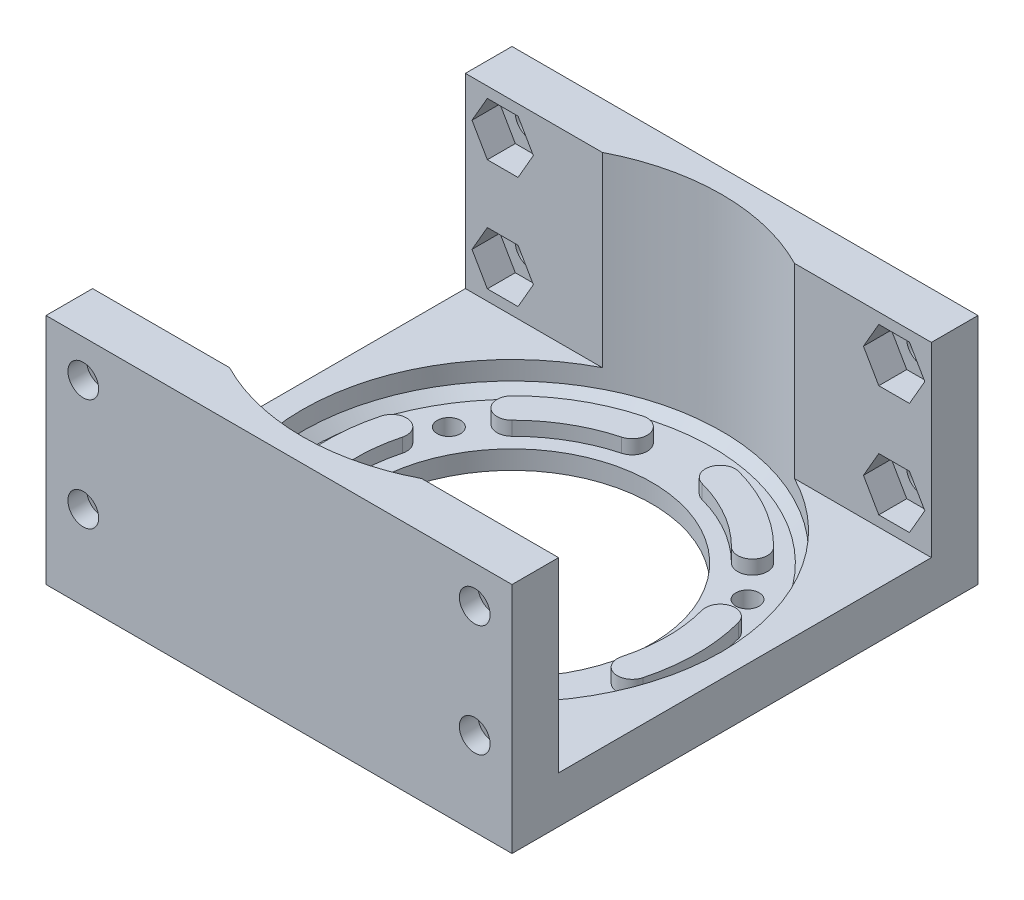
SolidWorks part; units mm, degrees
ref_plane "前视基准面" through (0, 0, 0) normal (0, 0, 1) x (1, 0, 0)
ref_plane "上视基准面" through (0, 0, 0) normal (0, 1, 0) x (1, 0, 0)
ref_plane "右视基准面" through (0, 0, 0) normal (1, 0, 0) x (0, 0, -1)
sketch "草图1" plane through (0, 0, 0) normal (0, 1, 0) x (1, 0, 0)
  line L15 (-25, 25) -> (25, 25)
  line L16 (-25, 25) -> (-25, -25)
  line L17 (-25, -25) -> (25, -25)
  line L18 (25, 25) -> (25, -25)
  line L19 (-25, 25) -> (25, -25) construction
  line L20 (-25, -25) -> (25, 25) construction
  point P0 (0, 0)
  dimension "D1" = 50
  dimension "D2" = 50
extrude "凸台-拉伸1" add sketch "草图1" along normal blind 5
sketch "草图2" plane through (0, 5, 0) normal (0, 1, 0) x (1, 0, 0)
  circle A0 centre (0, 0) radius 15
  point P0 (0, 0)
  dimension "D1" = 30
extrude "切除-拉伸1" cut sketch "草图2" against normal up to next
sketch "草图3" plane through (0, 5, 0) normal (0, 1, 0) x (1, 0, 0)
  circle A0 centre (0, 0) radius 22.5
  dimension "D1" = 45
extrude "切除-拉伸2" cut sketch "草图3" against normal offset from surface (3 mm away) 2 up to face at (0, 0, 15)
sketch "草图4" plane through (0, 2, 0) normal (0, 1, 0) x (1, 0, 0)
  line L0 (0, 0) -> (-16.0215, 9.25) construction
  line L1 (0, 0) -> (16.0215, 9.25) construction
  line L2 (0, 0) -> (0, -18.5) construction
  circle A0 centre (0, 0) radius 18.5 construction
  circle A1 centre (0, -18.5) radius 1.25
  circle A2 centre (-16.0215, 9.25) radius 1.25
  circle A3 centre (16.0215, 9.25) radius 1.25
  dimension "D1" = 37
  dimension "D4" = 2.5
  dimension "D2" = 120
  dimension "D3" = 120
extrude "切除-拉伸3" cut sketch "草图4" against normal up to next
chamfer "倒角1" distance 1 angle 45 1 edges at (0, 2, 22.5)
sketch "草图7" plane through (0, 2, 0) normal (0, 1, 0) x (1, 0, 0)
  line L0 (0, -18.25) -> (0, 0) construction
  line L1 (0, 0) -> (-9.125, -15.805) construction
  line L2 (0, 0) -> (-18.25, 0) construction
  line L3 (0, 0) -> (-9.125, 15.805) construction
  line L4 (0, 0) -> (9.125, 15.805) construction
  line L5 (0, 0) -> (18.25, 0) construction
  line L6 (0, 0) -> (9.125, -15.805) construction
  line L7 (-17.6281, -4.7234) -> (0, 0) construction
  circle A0 centre (0, 0) radius 18.25 construction
  arc A1 (-4.7234, 17.6281) -> (-12.9047, 12.9047) centre (0, 0) ccw construction
  arc A2 (-5.1376, 19.1736) -> (-14.0361, 14.0361) centre (0, 0) ccw
  arc A3 (-4.3093, 16.0827) -> (-11.7733, 11.7733) centre (0, 0) ccw
  arc A4 (-4.3093, 16.0827) -> (-5.1376, 19.1736) centre (-4.7234, 17.6281) ccw
  arc A5 (-14.0361, 14.0361) -> (-11.7733, 11.7733) centre (-12.9047, 12.9047) ccw
  arc A6 (4.7234, 17.6281) -> (12.9047, 12.9047) centre (0, 0) cw construction
  arc A7 (14.0361, 14.0361) -> (5.1376, 19.1736) centre (0, 0) ccw
  arc A8 (11.7733, 11.7733) -> (4.3093, 16.0827) centre (0, 0) ccw
  arc A9 (11.7733, 11.7733) -> (14.0361, 14.0361) centre (12.9047, 12.9047) ccw
  arc A10 (5.1376, 19.1736) -> (4.3093, 16.0827) centre (4.7234, 17.6281) ccw
  arc A11 (17.6281, 4.7234) -> (17.6281, -4.7234) centre (0, 0) cw construction
  arc A12 (19.1736, -5.1376) -> (19.1736, 5.1376) centre (0, 0) ccw
  arc A13 (16.0827, -4.3093) -> (16.0827, 4.3093) centre (0, 0) ccw
  arc A14 (16.0827, -4.3093) -> (19.1736, -5.1376) centre (17.6281, -4.7234) ccw
  arc A15 (19.1736, 5.1376) -> (16.0827, 4.3093) centre (17.6281, 4.7234) ccw
  arc A16 (12.9047, -12.9047) -> (4.7234, -17.6281) centre (0, 0) cw construction
  arc A17 (5.1376, -19.1736) -> (14.0361, -14.0361) centre (0, 0) ccw
  arc A18 (4.3093, -16.0827) -> (11.7733, -11.7733) centre (0, 0) ccw
  arc A19 (4.3093, -16.0827) -> (5.1376, -19.1736) centre (4.7234, -17.6281) ccw
  arc A20 (14.0361, -14.0361) -> (11.7733, -11.7733) centre (12.9047, -12.9047) ccw
  arc A21 (-4.7234, -17.6281) -> (-12.9047, -12.9047) centre (0, 0) cw construction
  arc A22 (-14.0361, -14.0361) -> (-5.1376, -19.1736) centre (0, 0) ccw
  arc A23 (-11.7733, -11.7733) -> (-4.3093, -16.0827) centre (0, 0) ccw
  arc A24 (-11.7733, -11.7733) -> (-14.0361, -14.0361) centre (-12.9047, -12.9047) ccw
  arc A25 (-5.1376, -19.1736) -> (-4.3093, -16.0827) centre (-4.7234, -17.6281) ccw
  arc A26 (-17.6281, -4.7234) -> (-17.6281, 4.7234) centre (0, 0) cw construction
  arc A27 (-19.1736, 5.1376) -> (-19.1736, -5.1376) centre (0, 0) ccw
  arc A28 (-16.0827, 4.3093) -> (-16.0827, -4.3093) centre (0, 0) ccw
  arc A29 (-16.0827, 4.3093) -> (-19.1736, 5.1376) centre (-17.6281, 4.7234) ccw
  arc A30 (-19.1736, -5.1376) -> (-16.0827, -4.3093) centre (-17.6281, -4.7234) ccw
  point P6 (-9.125, 15.805)
  point P11 (9.125, 15.805)
  point P19 (18.25, 0)
  point P27 (9.125, -15.805)
  point P35 (-9.125, -15.805)
  point P43 (-18.25, 0)
  dimension "D1" = 36.5
  dimension "D9" = 1.6
  dimension "D2" = 30
  dimension "D3" = 60
  dimension "D4" = 60
  dimension "D5" = 60
  dimension "D6" = 60
  dimension "D7" = 30
  dimension "D8" = 15
extrude "凸台-拉伸2" add sketch "草图7" along normal blind 1.5
sketch "草图8" plane through (0, 5, 0) normal (0, 1, 0) x (1, 0, 0)
  line L0 (-25, -25) -> (25, -25)
  line L1 (25, -25) -> (25, -20)
  line L2 (25, -25) -> (25, 25) construction
  line L3 (25, -20) -> (10.3078, -20)
  line L4 (-25, -25) -> (-25, -20)
  line L5 (-25, 25) -> (-25, -25) construction
  line L6 (-25, -20) -> (-10.3078, -20)
  circle A0 centre (0, 0) radius 22.5 construction
  circle A1 centre (0, 0) radius 22.5 construction
  arc A2 (-10.3078, -20) -> (10.3078, -20) centre (0, 0) ccw
  dimension "D1" = 5
extrude "凸台-拉伸3" add sketch "草图8" along normal blind 20
sketch "草图9" plane through (0, 0, 20) normal (0, 0, -1) x (-1, 0, 0)
  line L0 (25, 15) -> (21, 15) construction
  line L1 (25, 25) -> (25, 5) construction
  line L2 (21, 21) -> (21, 9) construction
  circle A0 centre (21, 21) radius 1.65
  circle A1 centre (21, 9) radius 1.65
  point P6 (21, 15)
  dimension "D3" = 3.3
  dimension "D1" = 12
  dimension "D2" = 4
extrude "切除-拉伸4" cut sketch "草图9" against normal up to next
sketch "草图10" plane through (0, 0, 20) normal (0, 0, -1) x (-1, 0, 0)
  line L1 (24.2909, 21) -> (22.6454, 23.85)
  line L2 (22.6454, 23.85) -> (19.3546, 23.85)
  line L3 (19.3546, 23.85) -> (17.7091, 21)
  line L4 (17.7091, 21) -> (19.3546, 18.15)
  line L5 (19.3546, 18.15) -> (22.6454, 18.15)
  line L6 (22.6454, 18.15) -> (24.2909, 21)
  line L7 (24.2909, 9) -> (22.6454, 11.85)
  line L8 (22.6454, 11.85) -> (19.3546, 11.85)
  line L9 (19.3546, 11.85) -> (17.7091, 9)
  line L10 (17.7091, 9) -> (19.3546, 6.15)
  line L11 (19.3546, 6.15) -> (22.6454, 6.15)
  line L12 (22.6454, 6.15) -> (24.2909, 9)
  circle A0 centre (21, 21) radius 2.85 construction
  circle A1 centre (21, 9) radius 2.85 construction
  dimension "D1" = 5.7
  dimension "D2" = 5.7
extrude "切除-拉伸5" cut sketch "草图10" against normal blind 3
mirror "镜向2" about plane through (0, 0, 0) normal (1, 0, 0) of "切除-拉伸5", "切除-拉伸4"
mirror "镜向1" about plane through (0, 0, 0) normal (0, 0, 1) of "凸台-拉伸3", "镜向2", "切除-拉伸4", "切除-拉伸5"
